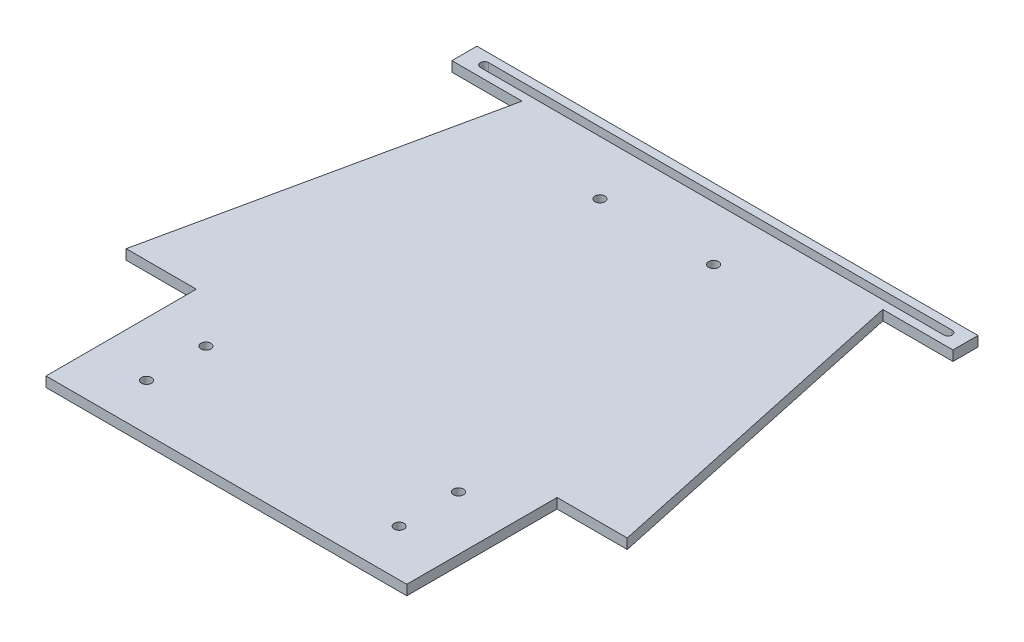
SolidWorks part; units mm, degrees
ref_plane "Front Plane" through (0, 0, 0) normal (0, 0, 1) x (1, 0, 0)
ref_plane "Top Plane" through (0, 0, 0) normal (0, 1, 0) x (1, 0, 0)
ref_plane "Right Plane" through (0, 0, 0) normal (1, 0, 0) x (0, 0, -1)
sketch "Esquisse1" plane through (0, 0, 0) normal (0, 1, 0) x (1, 0, 0)
  line L0 (0, 0) -> (28, 0)
  line L1 (28, 0) -> (0, -130)
  line L2 (0, -130) -> (28, -130)
  line L3 (28, -130) -> (28, -190)
  line L4 (28, -190) -> (172, -190)
  line L5 (172, -190) -> (172, -130)
  line L6 (172, -130) -> (200, -130)
  line L7 (200, -130) -> (172, 0)
  line L8 (172, 0) -> (200, 0)
  line L9 (200, 0) -> (200, 10)
  line L10 (200, 10) -> (0, 10)
  line L11 (0, 10) -> (0, 0)
  line L12 (100, 10) -> (100, -190) construction
  line L13 (8.0458, 5) -> (193.0458, 5) construction
  line L14 (8.0458, 6.6565) -> (193.0458, 6.6565)
  line L15 (8.0458, 3.3435) -> (193.0458, 3.3435)
  circle A0 centre (49.5822, -147.7692) radius 2
  circle A1 centre (49.5822, -171.4601) radius 2
  circle A2 centre (77.3056, -18.2255) radius 2
  circle A3 centre (150.4178, -171.4601) radius 2
  circle A4 centre (150.4178, -147.7692) radius 2
  circle A5 centre (122.6944, -18.2255) radius 2
  arc A6 (8.0458, 6.6565) -> (8.0458, 3.3435) centre (8.0458, 5) ccw
  arc A7 (193.0458, 3.3435) -> (193.0458, 6.6565) centre (193.0458, 5) ccw
  point P21 (100.5458, 5)
  dimension "D8" = 4
  dimension "D1" = 200
  dimension "D2" = 28
  dimension "D3" = 28
  dimension "D4" = 200
  dimension "D5" = 200
  dimension "D6" = 60
  dimension "D7" = 10
  dimension "D9" = 185
  dimension "D10" = 92.5
  dimension "D11" = 92.5
extrude "Boss.-Extru.1" add sketch "Esquisse1" along normal blind 4
